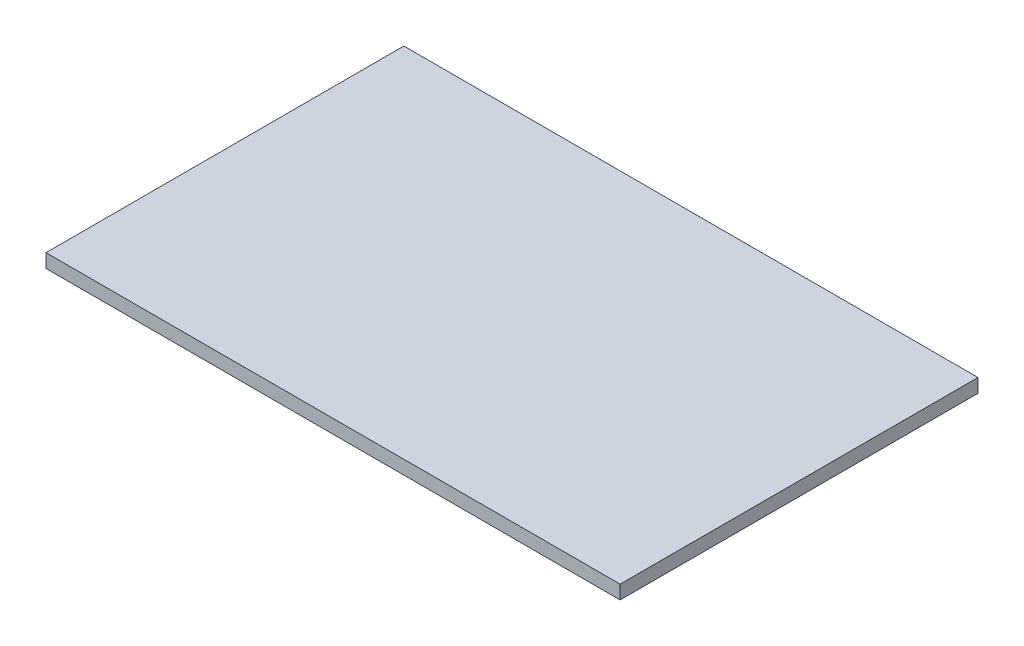
SolidWorks part; units mm, degrees
ref_plane "Front Plane" through (0, 0, 0) normal (0, 0, 1) x (1, 0, 0)
ref_plane "Top Plane" through (0, 0, 0) normal (0, 1, 0) x (1, 0, 0)
ref_plane "Right Plane" through (0, 0, 0) normal (1, 0, 0) x (0, 0, -1)
sketch "Sketch1" plane through (0, 0, 0) normal (0, 1, 0) x (1, 0, 0)
  line L1 (-377, 235) -> (377, 235)
  line L2 (-377, 235) -> (-377, -235)
  line L3 (-377, -235) -> (377, -235)
  line L4 (377, 235) -> (377, -235)
  line L5 (-377, 235) -> (377, -235) construction
  line L6 (-377, -235) -> (377, 235) construction
  point P0 (0, 0)
  dimension "D1" = 754
  dimension "D2" = 470
extrude "Boss-Extrude1" add sketch "Sketch1" along normal blind 18
equation "\"Case_Width\" = 790mm"
equation "\"Case_Depth\" = 470mm"
equation "\"WoodSheet_Thickness\" = 18mm"
equation "\"D1@Boss-Extrude1\"=\"WoodSheet_Thickness\""
equation "\"D1@Sketch1\"=\"Case_Width\"-(\"WoodSheet_Thickness\"*2)"
equation "\"D2@Sketch1\"=\"Case_Depth\""
